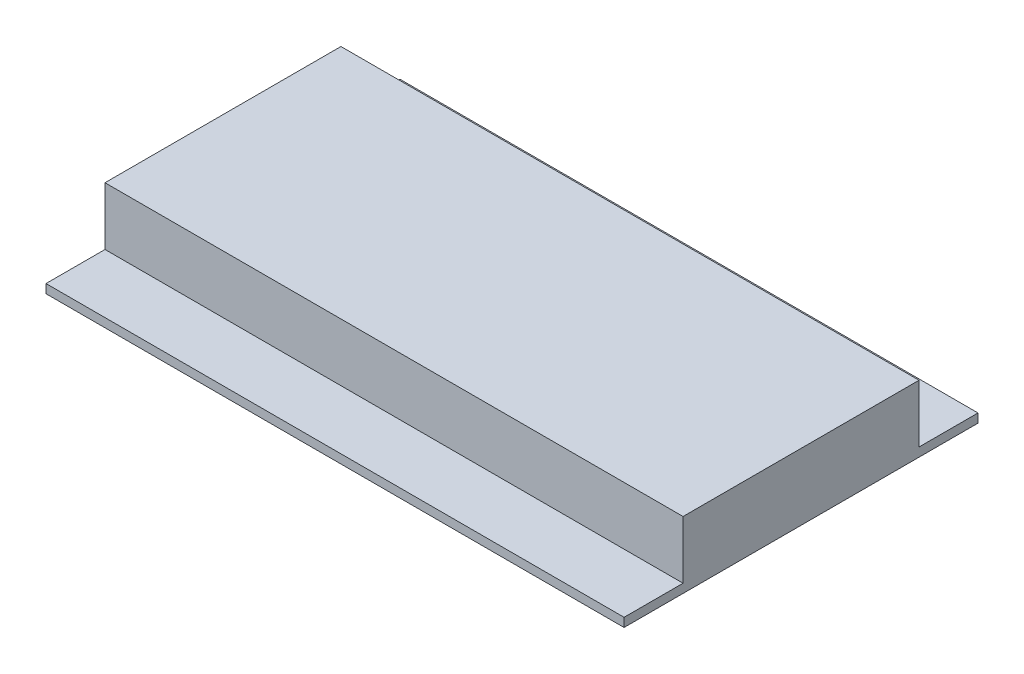
SolidWorks part; units mm, degrees
ref_plane "Front Plane" through (0, 0, 0) normal (0, 0, 1) x (1, 0, 0)
ref_plane "Top Plane" through (0, 0, 0) normal (0, 1, 0) x (1, 0, 0)
ref_plane "Right Plane" through (0, 0, 0) normal (1, 0, 0) x (0, 0, -1)
sketch "Sketch1" plane through (0, 0, 0) normal (0, 1, 0) x (1, 0, 0)
  line L1 (-49, 30) -> (49, 30)
  line L2 (-49, 30) -> (-49, -30)
  line L3 (-49, -30) -> (49, -30)
  line L4 (49, 30) -> (49, -30)
  point P4 (0, 30)
  point P6 (49, 0)
  dimension "D1" = 60
  dimension "D2" = 98
extrude "Boss-Extrude1" add sketch "Sketch1" along normal blind 1.5
sketch "Sketch2" plane through (0, 1.5, 0) normal (0, 1, 0) x (1, 0, 0)
  line L0 (-49, 30) -> (-49, -30) construction
  line L1 (-49, 20) -> (49, 20)
  line L2 (-49, 20) -> (-49, -20)
  line L3 (-49, -20) -> (49, -20)
  line L4 (49, 20) -> (49, -20)
  line L5 (49, -30) -> (49, 30) construction
  line L6 (-49, -30) -> (49, -30) construction
  dimension "D1" = 40
  dimension "D2" = 10
extrude "Boss-Extrude2" add sketch "Sketch2" along normal blind 9.8
